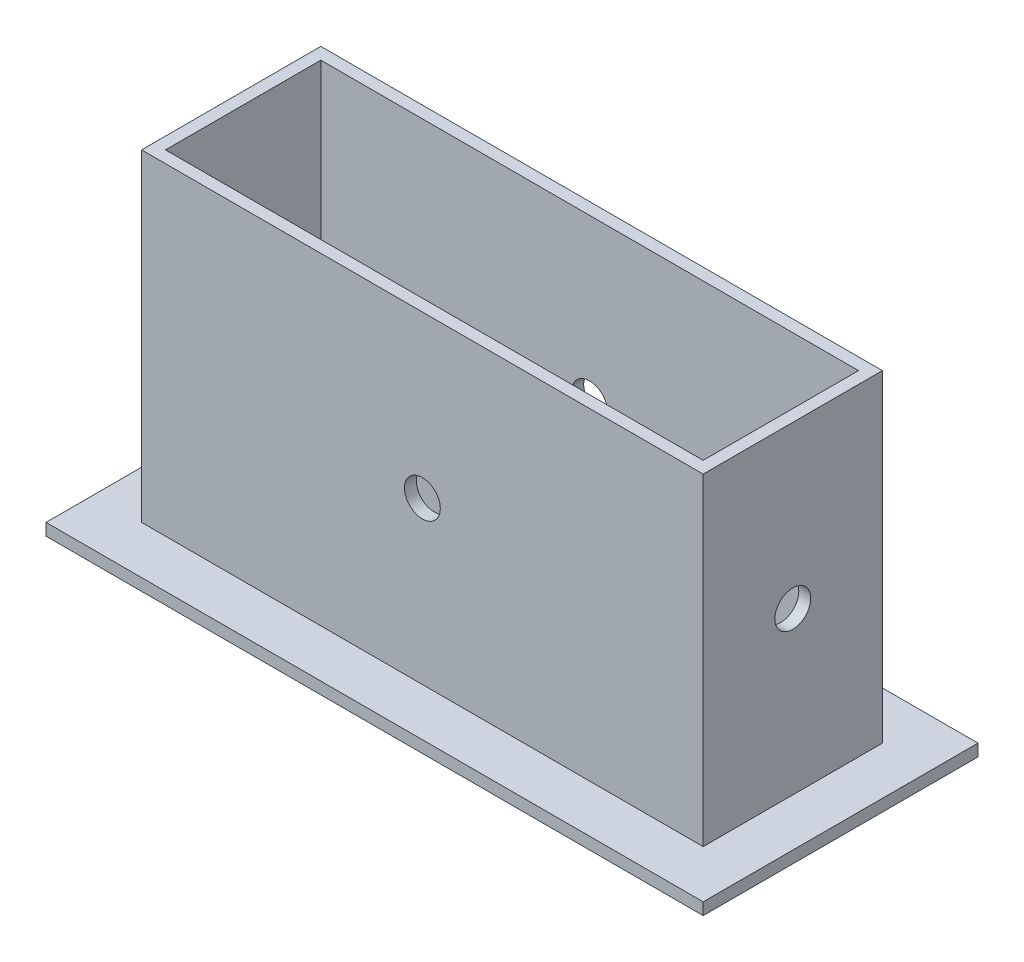
SolidWorks part; units mm, degrees
ref_plane "Front Plane" through (0, 0, 0) normal (0, 0, 1) x (1, 0, 0)
ref_plane "Top Plane" through (0, 0, 0) normal (0, 1, 0) x (1, 0, 0)
ref_plane "Right Plane" through (0, 0, 0) normal (1, 0, 0) x (0, 0, -1)
sketch "Sketch1" plane through (0, 0, 0) normal (0, 0, 1) x (1, 0, 0)
  line L1 (-23.5, 13.5) -> (23.5, 13.5)
  line L2 (-23.5, 13.5) -> (-23.5, -13.5)
  line L3 (-23.5, -13.5) -> (23.5, -13.5)
  line L4 (23.5, 13.5) -> (23.5, -13.5)
  point P7 (0.3389, -4.7452)
  dimension "D1" = 47
  dimension "D2" = 27
  dimension "D3" = 23.5
  dimension "D4" = 13.5
extrude "Boss-Extrude1" add sketch "Sketch1" along normal blind 15
sketch "Sketch2" plane through (0, 13.5, 0) normal (0, 1, 0) x (1, 0, 0)
  line L0 (-23.5, -15) -> (-23.5, 0) construction
  line L1 (-22.5, -1) -> (22.5, -1)
  line L2 (-22.5, -1) -> (-22.5, -14)
  line L3 (-22.5, -14) -> (22.5, -14)
  line L4 (22.5, -1) -> (22.5, -14)
  line L5 (23.5, 0) -> (-23.5, 0) construction
  line L6 (23.5, -15) -> (-23.5, -15) construction
  line L7 (23.5, -15) -> (23.5, 0) construction
  dimension "D1" = 1
  dimension "D2" = 1
  dimension "D3" = 1
  dimension "D4" = 1
extrude "Cut-Extrude1" cut sketch "Sketch2" against normal blind 27
sketch "Sketch3" plane through (0, -13.5, 0) normal (0, -1, 0) x (1, 0, 0)
  line L0 (-23.5, 15) -> (-23.5, 0) construction
  line L1 (-27.5, 19) -> (27.5, 19)
  line L2 (-27.5, 19) -> (-27.5, -4)
  line L3 (-27.5, -4) -> (27.5, -4)
  line L4 (27.5, 19) -> (27.5, -4)
  line L5 (-22.5, 14) -> (22.5, 14)
  line L6 (-22.5, 14) -> (-22.5, 1)
  line L7 (-22.5, 1) -> (22.5, 1)
  line L8 (22.5, 14) -> (22.5, 1)
  line L9 (-23.5, 15) -> (23.5, 15) construction
  line L10 (-23.5, 0) -> (23.5, 0) construction
  line L11 (23.5, 15) -> (23.5, 0) construction
  dimension "D1" = 4
  dimension "D2" = 4
  dimension "D3" = 4
  dimension "D4" = 4
extrude "Boss-Extrude2" add sketch "Sketch3" along normal blind 1
sketch "Sketch4" plane through (0, 0, 15) normal (0, 0, 1) x (1, 0, 0)
  circle A0 centre (0, 0) radius 1.5
  dimension "D1" = 3
extrude "Cut-Extrude2" cut sketch "Sketch4" against normal blind 17
sketch "Sketch5" plane through (-23.5, 0, 0) normal (-1, 0, 0) x (0, 0, 1)
  line L0 (0, 13.5) -> (0, -13.5) construction
  line L1 (15, 13.5) -> (0, 13.5) construction
  circle A0 centre (7.5, 0) radius 1.5
  dimension "D2" = 3
  dimension "D1" = 7.5
  dimension "D3" = 13.5
extrude "Cut-Extrude3" cut sketch "Sketch5" against normal blind 47
